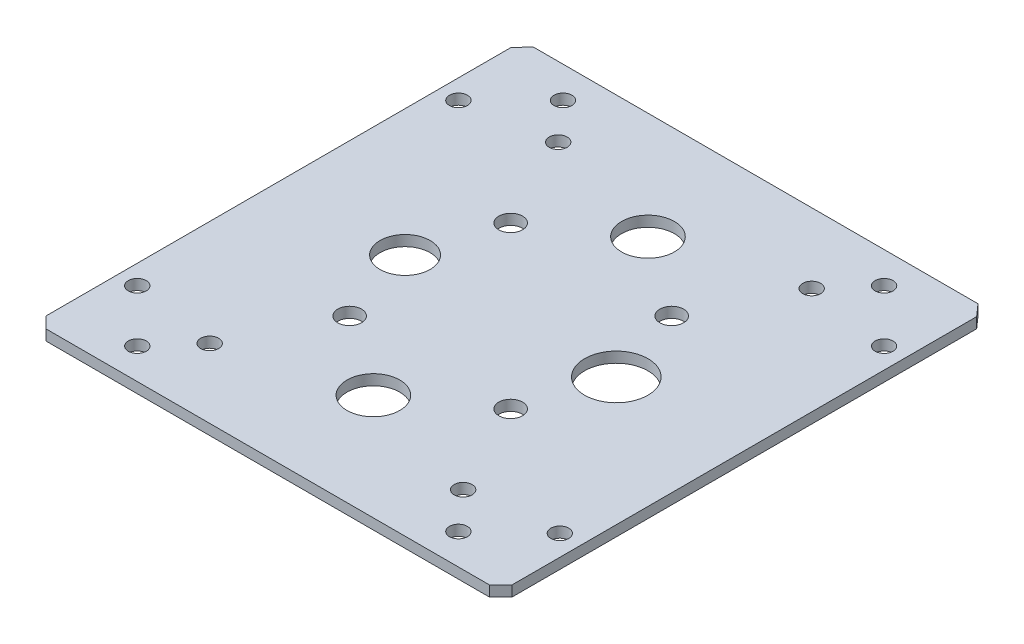
SolidWorks part; units mm, degrees
ref_plane "前视基准面" through (0, 0, 0) normal (0, 0, 1) x (1, 0, 0)
ref_plane "上视基准面" through (0, 0, 0) normal (0, 1, 0) x (1, 0, 0)
ref_plane "右视基准面" through (0, 0, 0) normal (1, 0, 0) x (0, 0, -1)
other "Configuration Table"
sketch "草图1" plane through (0, 0, 0) normal (0, 1, 0) x (1, 0, 0)
  line L0 (-41.8787, -46.1213) -> (42.1213, -46.1213)
  line L1 (42.1213, -46.1213) -> (44.2385, -43.9959)
  line L2 (44.2385, -43.9959) -> (44.2385, 44.0041)
  line L3 (44.2385, 44.0041) -> (42.2495, 46.25)
  line L4 (42.2495, 46.25) -> (-42.0157, 46.25)
  line L5 (-42.0157, 46.25) -> (-44, 44)
  line L6 (-44, 44) -> (-44, -44)
  line L7 (-44, -44) -> (-41.8787, -46.1213)
  line L8 (-40.3051, 30.4056) -> (-30.4056, 40.3051) construction
  line L9 (0, 0) -> (75.4458, 0) construction
  line L10 (0, 0) -> (0, 38.6741) construction
  circle A0 centre (-15.25, -15.25) radius 2.25
  circle A1 centre (-15.25, 15.25) radius 2.25
  circle A2 centre (15.25, -15.25) radius 2.25
  circle A3 centre (15.25, 15.25) radius 2.25
  circle A4 centre (-24, -33) radius 1.7
  circle A8 centre (20, 0) radius 6
  circle A9 centre (-20, 0) radius 4.75
  circle A10 centre (0, 26) radius 5
  circle A11 centre (0, -26) radius 5
  circle A13 centre (-30.4056, -40.3051) radius 1.7
  circle A14 centre (-30.4056, 40.3051) radius 1.7
  circle A15 centre (-40.3051, 30.4056) radius 1.7
  circle A16 centre (30.4056, -40.3051) radius 1.7
  circle A17 centre (40.3051, -31) radius 1.6949
  circle A18 centre (40.3051, 30.4056) radius 1.6949
  circle A19 centre (30.4056, 40.3051) radius 1.7
  circle A20 centre (-40.3051, -30.4056) radius 1.7
  circle A21 centre (24, -33) radius 1.7
  circle A22 centre (24, 33) radius 1.7
  circle A23 centre (-24, 33) radius 1.7
  dimension "D3" = 4.5
  dimension "D4" = 4.5
  dimension "D14" = 3.4
  dimension "D1" = 88
  dimension "D2" = 84
  dimension "D5" = 3
  dimension "D6" = 3
  dimension "D7" = 3
  dimension "D8" = 3
  dimension "D9" = 26
  dimension "D10" = 20
  dimension "D11" = 40.3051
  dimension "D12" = 24
  dimension "D13" = 33
extrude "凸台-拉伸1" add sketch "草图1" along normal blind 2
